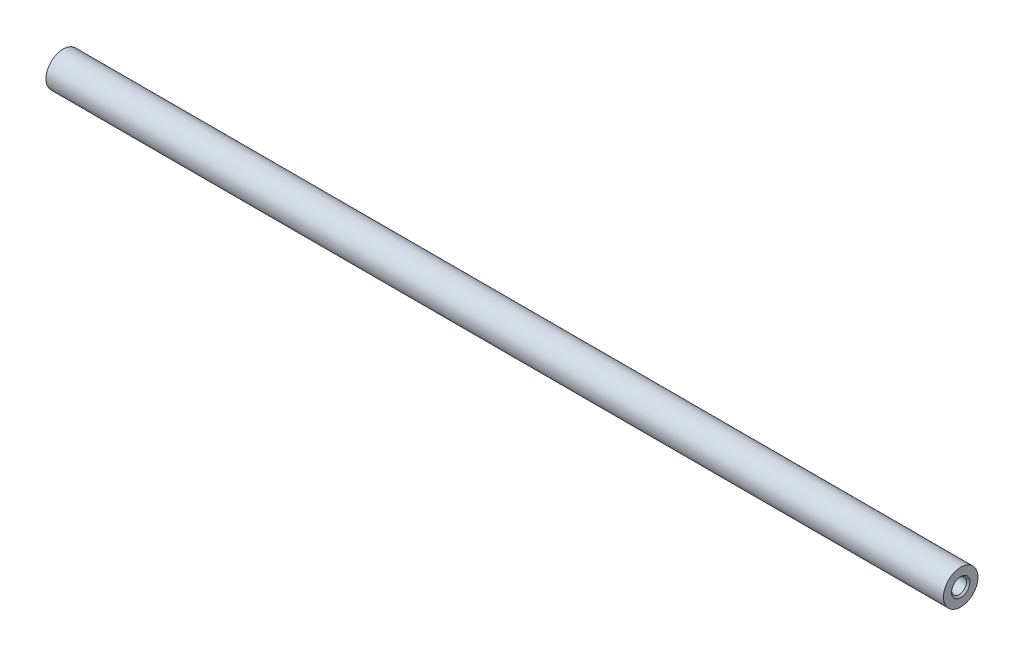
SolidWorks part; units mm, degrees
ref_plane "前视基准面" through (0, 0, 0) normal (0, 0, 1) x (1, 0, 0)
ref_plane "上视基准面" through (0, 0, 0) normal (0, 1, 0) x (1, 0, 0)
ref_plane "右视基准面" through (0, 0, 0) normal (1, 0, 0) x (0, 0, -1)
sketch "草图1" plane through (0, 0, 0) normal (1, 0, 0) x (0, 0, -1)
  circle A0 centre (0, 0) radius 10
  dimension "D1" = 20
extrude "拉伸1" add sketch "草图1" along normal blind 520
sketch "草图2" plane through (520, 0, 0) normal (1, 0, 0) x (0, 0, -1)
  circle A0 centre (0, 0) radius 4.3
  dimension "D1" = 8.6
extrude "拉伸2" cut sketch "草图2" against normal blind 25
chamfer "倒角1" distance 1 angle 45 1 edges at (520, 0, -4.3)
